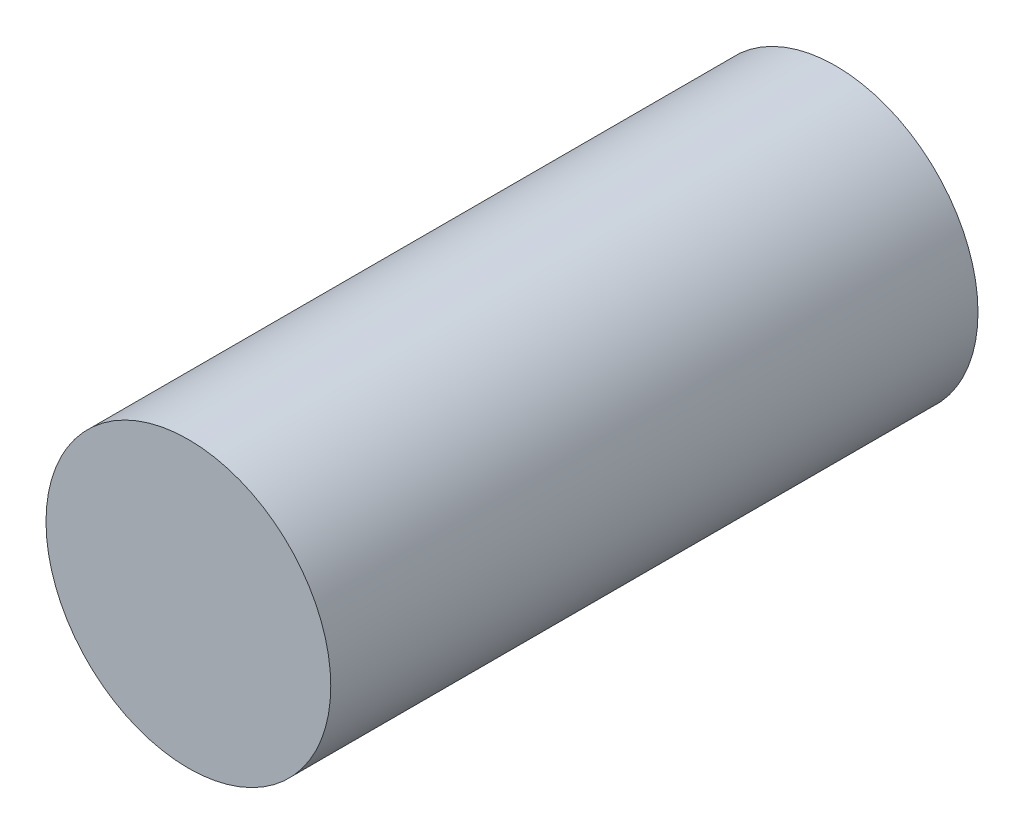
SolidWorks part; units mm, degrees
ref_plane "Front Plane" through (0, 0, 0) normal (0, 0, 1) x (1, 0, 0)
ref_plane "Top Plane" through (0, 0, 0) normal (0, 1, 0) x (1, 0, 0)
ref_plane "Right Plane" through (0, 0, 0) normal (1, 0, 0) x (0, 0, -1)
sketch "Sketch1" plane through (0, 0, 0) normal (0, 0, 1) x (1, 0, 0)
  circle A0 centre (0, 0) radius 27.5
  dimension "D1" = 55
extrude "Boss-Extrude3" add sketch "Sketch1" along normal blind 125 contours A0
